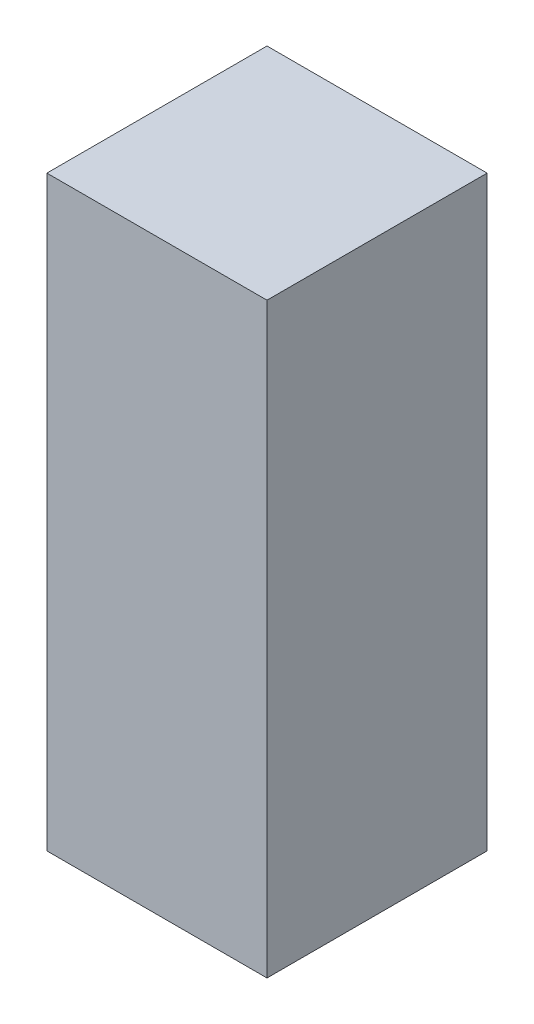
SolidWorks part; units mm, degrees
ref_plane "Front Plane" through (0, 0, 0) normal (0, 0, 1) x (1, 0, 0)
ref_plane "Top Plane" through (0, 0, 0) normal (0, 1, 0) x (1, 0, 0)
ref_plane "Right Plane" through (0, 0, 0) normal (1, 0, 0) x (0, 0, -1)
sketch "Sketch2" plane through (0, 0, 0) normal (0, 1, 0) x (1, 0, 0)
  line L1 (-38.1, -38.1) -> (38.1, -38.1)
  line L2 (-38.1, -38.1) -> (-38.1, 38.1)
  line L3 (-38.1, 38.1) -> (38.1, 38.1)
  line L4 (38.1, -38.1) -> (38.1, 38.1)
  line L5 (-38.1, -38.1) -> (38.1, 38.1) construction
  line L6 (-38.1, 38.1) -> (38.1, -38.1) construction
  line L7 (-36.83, -36.83) -> (36.83, -36.83)
  line L8 (-36.83, -36.83) -> (-36.83, 36.83)
  line L9 (-36.83, 36.83) -> (36.83, 36.83)
  line L10 (36.83, -36.83) -> (36.83, 36.83)
  line L11 (-36.83, -36.83) -> (36.83, 36.83) construction
  line L12 (-36.83, 36.83) -> (36.83, -36.83) construction
  point P0 (0, 0)
  point P6 (0, 0)
  dimension "D1" = 76.2
  dimension "D2" = 76.2
  dimension "D3" = 73.66
  dimension "D4" = 73.66
extrude "Boss-Extrude1" add sketch "Sketch2" along normal blind 203.2
sketch "Sketch3" plane through (0, 203.2, 0) normal (0, 1, 0) x (1, 0, 0)
  line L1 (-36.83, -36.83) -> (36.83, -36.83)
  line L2 (-36.83, -36.83) -> (-36.83, 36.83)
  line L3 (-36.83, 36.83) -> (36.83, 36.83)
  line L4 (36.83, -36.83) -> (36.83, 36.83)
  line L5 (-36.83, -36.83) -> (36.83, 36.83) construction
  line L6 (-36.83, 36.83) -> (36.83, -36.83) construction
  point P0 (0, 0)
extrude "Boss-Extrude2" add sketch "Sketch3" against normal blind 1.27
